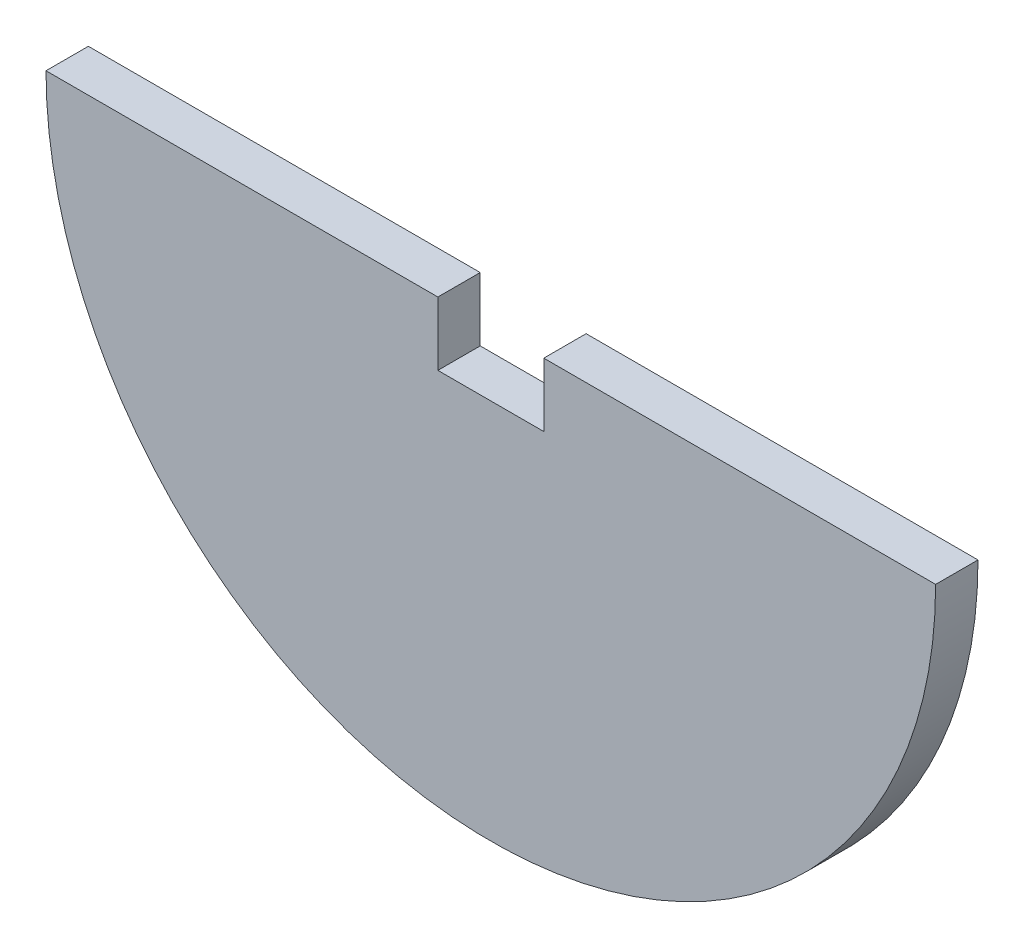
SolidWorks part; units mm, degrees
ref_plane "前视基准面" through (0, 0, 0) normal (0, 0, 1) x (1, 0, 0)
ref_plane "上视基准面" through (0, 0, 0) normal (0, 1, 0) x (1, 0, 0)
ref_plane "右视基准面" through (0, 0, 0) normal (1, 0, 0) x (0, 0, -1)
sketch "草图1" plane through (0, 0, 0) normal (0, 0, 1) x (1, 0, 0)
  line L0 (-25, 0) -> (-210, 0)
  line L1 (-210, 0) -> (-25, 0)
  line L3 (25, 0) -> (25, -30)
  line L4 (-25, 0) -> (-25, -30)
  line L6 (25, 0) -> (210, 0)
  line L7 (0, -30) -> (25, -30)
  line L8 (25, -30) -> (-25, -30)
  arc A1 (-210, 0) -> (210, 0) centre (0, 0) ccw
  point P12 (0, 0)
extrude "凸台-拉伸2" add sketch "草图1" along normal blind 20 contours L0 A1 L6 L3 L7 L8 L4
scale "缩放比例1" scale about centroid uniform scaling yes scale factor 0.5
